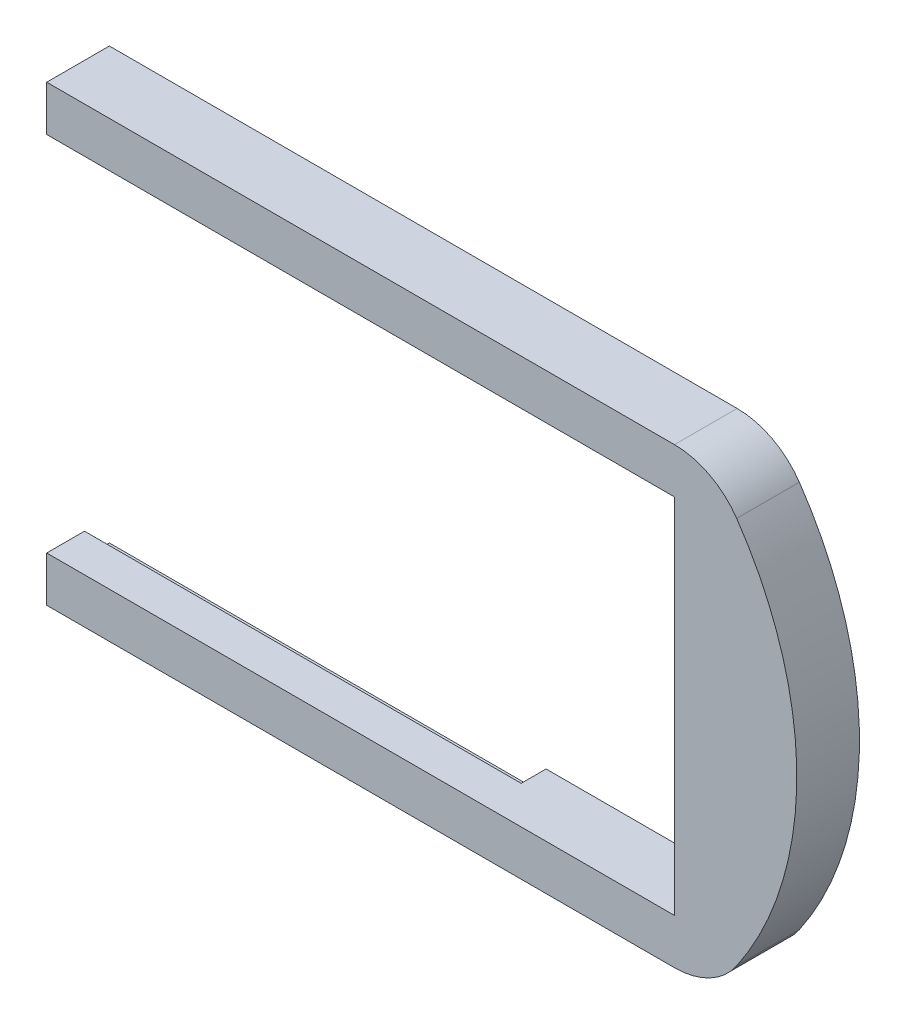
SolidWorks part; units mm, degrees
ref_plane "前视基准面" through (0, 0, 0) normal (0, 0, 1) x (1, 0, 0)
ref_plane "上视基准面" through (0, 0, 0) normal (0, 1, 0) x (1, 0, 0)
ref_plane "右视基准面" through (0, 0, 0) normal (1, 0, 0) x (0, 0, -1)
sketch "草图1" plane through (0, 0, 0) normal (0, 0, 1) x (1, 0, 0)
  line L0 (-49.1722, -29.541) -> (33.9677, -29.541)
  line L1 (33.9677, 30.459) -> (-49.1722, 30.459)
  line L2 (-49.1722, -26.541) -> (33.9677, -26.541)
  line L3 (33.9677, 27.459) -> (-49.1722, 27.459)
  line L4 (-49.1722, -29.541) -> (-49.1722, -26.541)
  line L5 (-49.1722, 30.459) -> (-49.1722, 27.459)
  line L6 (39.7391, 24.4201) -> (39.7391, -23.5022)
  line L7 (8.6677, 27.459) -> (8.6677, 24.4201)
  line L8 (8.6677, 24.4201) -> (39.7391, 24.4201)
  line L9 (8.6677, -23.541) -> (39.7391, -23.541)
  line L10 (8.6677, -23.541) -> (8.6677, -26.541)
  arc A0 (33.9677, -29.541) -> (42.2126, -25.1998) centre (33.9677, -19.541) ccw
  arc A1 (42.2126, -25.1998) -> (42.2126, 26.1178) centre (4.8278, 0.459) ccw
  arc A2 (42.2126, 26.1178) -> (33.9677, 30.459) centre (33.9677, 20.459) ccw
  arc A3 (33.9677, -26.541) -> (39.7391, -23.5022) centre (33.9677, -19.541) ccw
  arc A5 (39.7391, 24.4201) -> (33.9677, 27.459) centre (33.9677, 20.459) ccw
  arc A6 (39.7391, -23.5022) -> (39.7391, 24.4201) centre (4.8278, 0.459) ccw construction
  dimension "D1" = 83.14
  dimension "D3" = 25.3
  dimension "D4" = 3
  dimension "D2" = 3
extrude "凸台-拉伸1" add sketch "草图1" along normal blind 3.3
sketch "草图2" plane through (0, 0, 3.3) normal (0, 0, 1) x (1, 0, 0)
  line L11 (-49.1722, 27.459) -> (-49.1722, 24.459)
  line L12 (-49.1722, 24.459) -> (33.9677, 24.459)
  line L13 (33.9677, 24.459) -> (33.9677, -23.541)
  line L14 (33.9677, -23.541) -> (-49.1722, -23.541)
  line L15 (-49.1722, -23.541) -> (-49.1722, -26.541)
  line L22 (39.7391, 24.4201) -> (39.7391, -23.5022)
  line L23 (39.7123, -23.541) -> (8.6677, -23.541)
  line L24 (8.6677, -23.541) -> (8.6677, -26.541)
  line L25 (8.6677, -26.541) -> (-49.1722, -26.541)
  line L26 (-49.1722, -26.541) -> (-49.1722, -29.541)
  line L27 (-49.1722, -29.541) -> (33.9677, -29.541)
  line L28 (33.9677, 30.459) -> (-49.1722, 30.459)
  line L29 (-49.1722, 30.459) -> (-49.1722, 27.459)
  line L30 (-49.1722, 27.459) -> (8.6677, 27.459)
  line L31 (8.6677, 27.459) -> (8.6677, 24.4201)
  line L32 (39.7123, -23.541) -> (8.6677, -23.541)
  line L37 (-49.1722, -26.541) -> (-49.1722, -29.541)
  line L38 (-49.1722, -29.541) -> (33.9677, -29.541)
  line L39 (33.9677, 30.459) -> (-49.1722, 30.459)
  line L40 (-49.1722, 30.459) -> (-49.1722, 27.459)
  line L49 (8.6677, 24.4201) -> (39.7391, 24.4201)
  line L50 (8.6677, 24.4201) -> (39.7391, 24.4201)
  arc A6 (33.9677, -29.541) -> (42.2126, -25.1998) centre (33.9677, -19.541) ccw
  arc A7 (42.2126, -25.1998) -> (42.2126, 26.1178) centre (4.8278, 0.459) ccw
  arc A8 (42.2126, 26.1178) -> (33.9677, 30.459) centre (33.9677, 20.459) ccw
  arc A9 (33.9677, -29.541) -> (42.2126, -25.1998) centre (33.9677, -19.541) ccw
  arc A10 (42.2126, -25.1998) -> (42.2126, 26.1178) centre (4.8278, 0.459) ccw
  arc A11 (42.2126, 26.1178) -> (33.9677, 30.459) centre (33.9677, 20.459) ccw
  arc A13 (39.7123, -23.541) -> (39.7391, -23.5022) centre (33.9677, -19.541) ccw
  arc A14 (39.7123, -23.541) -> (39.7391, -23.5022) centre (33.9677, -19.541) ccw
  line M17 (39.7391, 24.4201) -> (39.7391, -23.5022)
  line M19 (8.6677, -23.541) -> (8.6677, -26.541)
  line M20 (8.6677, -26.541) -> (-49.1722, -26.541)
  line M21 (-49.1722, -26.541) -> (-49.1722, -29.541)
  line M22 (-49.1722, -29.541) -> (33.9677, -29.541)
  arc M23 (33.9677, -29.541) -> (42.2126, -25.1998) centre (33.9677, -19.541) ccw
  arc M24 (42.2126, -25.1998) -> (42.2126, 26.1178) centre (4.8278, 0.459) ccw
  arc M25 (42.2126, 26.1178) -> (33.9677, 30.459) centre (33.9677, 20.459) ccw
  line M26 (33.9677, 30.459) -> (-49.1722, 30.459)
  line M27 (-49.1722, 30.459) -> (-49.1722, 27.459)
  line M28 (-49.1722, 27.459) -> (8.6677, 27.459)
  line M29 (8.6677, 27.459) -> (8.6677, 24.4201)
  arc M34 (39.7391, -23.5022) -> (39.7123, -23.541) centre (33.9677, -19.541) cw
  line M35 (39.7123, -23.541) -> (8.6677, -23.541)
  line M36 (8.6677, 24.4201) -> (39.7391, 24.4201)
  dimension "D2" = 6
  dimension "D3" = 6
  dimension "D1" = 0
extrude "凸台-拉伸2" add sketch "草图2" along normal blind 5 contours L14 L15 M20 M19 | L13 M36 M35 M34 M17 | L12 L13 M36 M17 M34 M35 M19 M20 M21 M22 M23 M24 M25 M26 M27 M28 M29 | L11 L12 M29 M28
